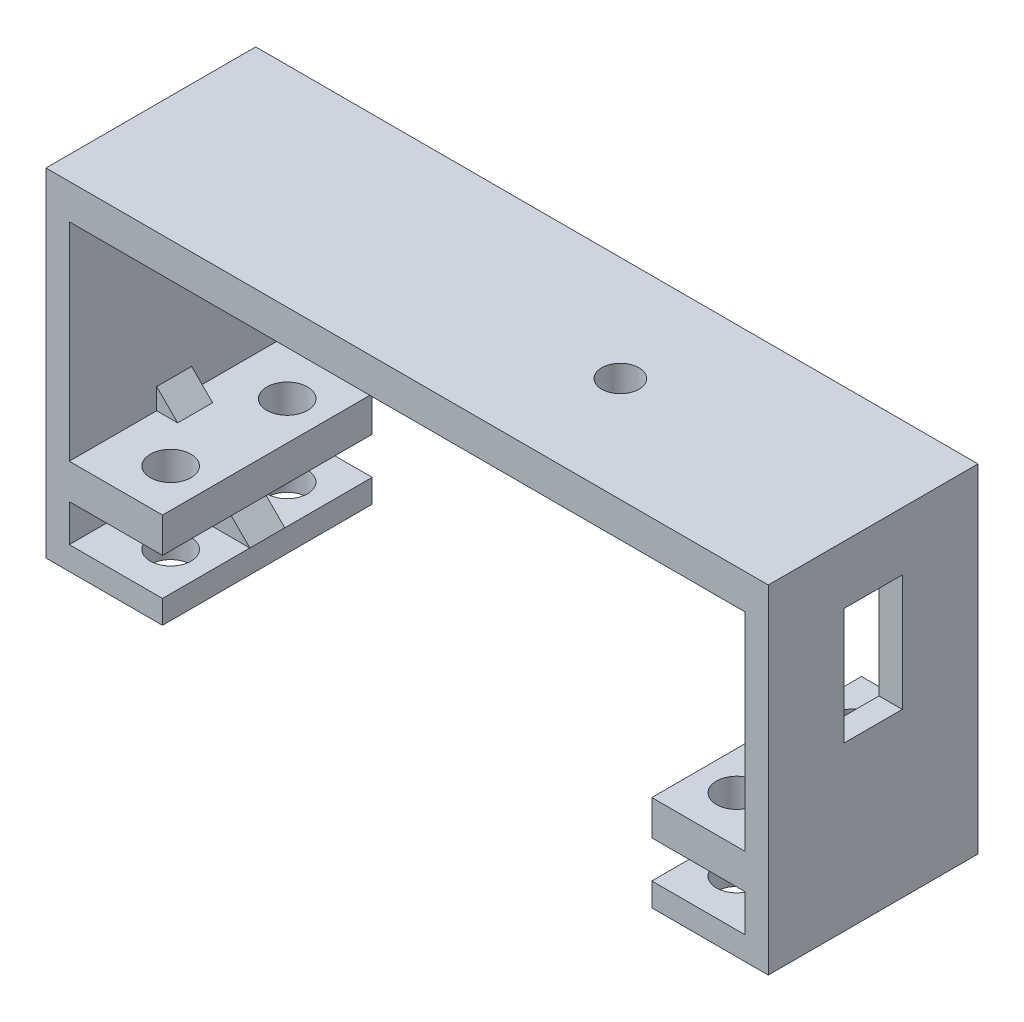
SolidWorks part; units mm, degrees
ref_plane "Plano frontal" through (0, 0, 0) normal (0, 0, 1) x (1, 0, 0)
ref_plane "Plano superior" through (0, 0, 0) normal (0, 1, 0) x (1, 0, 0)
ref_plane "Plano direito" through (0, 0, 0) normal (1, 0, 0) x (0, 0, -1)
sketch "Esboço1" plane through (0, 0, 0) normal (0, 0, 1) x (1, 0, 0)
  line L0 (-21, 0) -> (-31, 0)
  line L1 (-29, 2) -> (-29, 26)
  line L2 (-29, 26) -> (29, 26)
  line L3 (21, 2) -> (21, 0)
  line L4 (29, 2) -> (21, 2)
  line L5 (31, 29) -> (31, 0)
  line L6 (29, 2) -> (29, 26)
  line L7 (21, 0) -> (31, 0)
  line L8 (31, 29) -> (-31, 29)
  line L9 (-31, 29) -> (-31, 0)
  line L10 (-29, 2) -> (-21, 2)
  line L11 (-21, 2) -> (-21, 0)
  line L12 (0, 0) -> (0, 33.1059) construction
  point P14 (0, 29)
  point P16 (0, 26)
  dimension "D1" = 3
  dimension "D2" = 2
  dimension "D3" = 42
  dimension "D4" = 29
  dimension "D5" = 2
  dimension "D6" = 8
extrude "Ressalto-extrusão1" add sketch "Esboço1" along normal mid plane 18
sketch "Esboço2" plane through (0, 0, 0) normal (0, -1, 0) x (1, 0, 0)
  line L0 (0, 0) -> (0, 9) construction
  line L1 (-24.3, 5) -> (-24.3, -5) construction
  line L2 (-31, 9) -> (-31, -9) construction
  line L3 (24.3, 5) -> (24.3, -5) construction
  line L4 (-29, 9) -> (29, 9) construction
  circle A0 centre (-24.3, -5) radius 1.75
  circle A1 centre (-24.3, 5) radius 1.75
  circle A2 centre (24.3, 5) radius 1.75
  circle A3 centre (24.3, -5) radius 1.75
  point P7 (-24.3, 0)
  point P10 (-31, 0)
  dimension "D2" = 3.5
  dimension "D3" = 48.6
  dimension "D1" = 10
extrude "Corte-extrusão1" cut sketch "Esboço2" against normal blind 16
sketch "Esboço4" plane through (0, 0, 0) normal (0, 0, 1) x (1, 0, 0)
  line L0 (-21, 2) -> (-29, 10)
  line L1 (-29, 2) -> (-29, 26) construction
  line L2 (-29, 10) -> (-29, 2)
  line L3 (-29, 2) -> (-21, 2)
  line L4 (21, 2) -> (29, 2)
  line L5 (29, 2) -> (29, 10)
  line L6 (29, 26) -> (29, 2) construction
  line L7 (29, 10) -> (21, 2)
extrude "Ressalto-extrusão3" add sketch "Esboço4" along normal mid plane 3
sketch "Esboço6" plane through (0, 29, 0) normal (0, 1, 0) x (1, 0, 0)
  circle A0 centre (9.3, 0) radius 1.6
  circle A1 centre (24.3, -5) radius 1.75 construction
  dimension "D1" = 15
  dimension "D2" = 3.2
extrude "Corte-extrusão2" cut sketch "Esboço6" against normal blind 3
sketch "Esboço7" plane through (31, 0, 0) normal (1, 0, 0) x (0, 0, -1)
  line L0 (-9, 0) -> (9, 0) construction
  line L1 (2.5, 24) -> (-2.5, 24)
  line L2 (2.5, 24) -> (2.5, 14)
  line L3 (2.5, 14) -> (-2.5, 14)
  line L4 (-2.5, 24) -> (-2.5, 14)
  line L5 (2.5, 24) -> (-2.5, 14) construction
  line L6 (2.5, 14) -> (-2.5, 24) construction
  point P0 (0, 19)
  point P8 (0, 0)
  dimension "D1" = 24
  dimension "D2" = 5
  dimension "D3" = 10
extrude "Corte-extrusão3" cut sketch "Esboço7" against normal blind 10
sketch "Esboço8" plane through (0, 2, 0) normal (0, 1, 0) x (1, 0, 0)
  line L0 (-29, 9) -> (-21, 9)
  line L1 (-21, 9) -> (-21, -9)
  line L2 (-21, -9) -> (-29, -9)
  line L3 (-29, -9) -> (-29, 9)
  line L4 (0, 9) -> (0, -9) construction
  line L5 (29, -9) -> (29, 9)
  line L6 (21, -9) -> (29, -9)
  line L7 (21, 9) -> (21, -9)
  line L8 (29, 9) -> (21, 9)
  circle A0 centre (24.3, -5) radius 1.75 construction
  circle A1 centre (24.3, 5) radius 1.75 construction
  circle A2 centre (-24.3, -5) radius 1.75 construction
  circle A3 centre (-24.3, 5) radius 1.75 construction
  circle A4 centre (24.3, -5) radius 1.75
  circle A5 centre (24.3, 5) radius 1.75
  circle A6 centre (-24.3, -5) radius 1.75
  circle A7 centre (-24.3, 5) radius 1.75
extrude "Ressalto-extrusão4" add sketch "Esboço8" along normal blind 3 from offset 3.2
